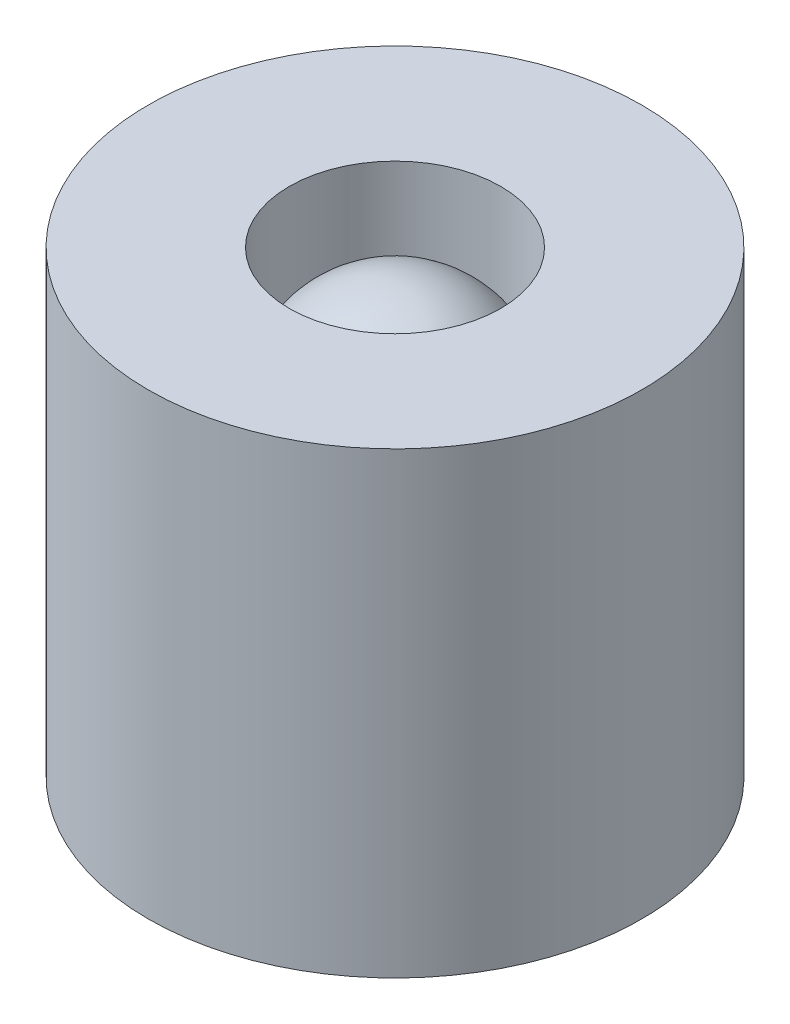
SolidWorks part; units mm, degrees
ref_plane "前视基准面" through (0, 0, 0) normal (0, 0, 1) x (1, 0, 0)
ref_plane "上视基准面" through (0, 0, 0) normal (0, 1, 0) x (1, 0, 0)
ref_plane "右视基准面" through (0, 0, 0) normal (1, 0, 0) x (0, 0, -1)
sketch "草图1" plane through (0, 0, 0) normal (0, 1, 0) x (1, 0, 0)
  circle A0 centre (0, 0) radius 3.5
  circle A1 centre (0, 0) radius 1.5
  dimension "D1" = 7
  dimension "D2" = 3
extrude "凸台-拉伸1" add sketch "草图1" along normal blind 6.5
ref_plane "基准面1" through (0, 4.5, 0) normal (0, 1, 0) x (1, 0, 0)
sketch "草图3" plane through (0, 4.5, 0) normal (0, 1, 0) x (1, 0, 0)
  line L0 (-3.959, 0) -> (6.1995, 0) construction
  line L1 (-1.55, 0) -> (1.55, 0)
  arc A0 (-1.55, 0) -> (1.55, 0) centre (0, 0) ccw
  dimension "D1" = 3.1
revolve "旋转5" add sketch "草图3" angle 360 about L0
